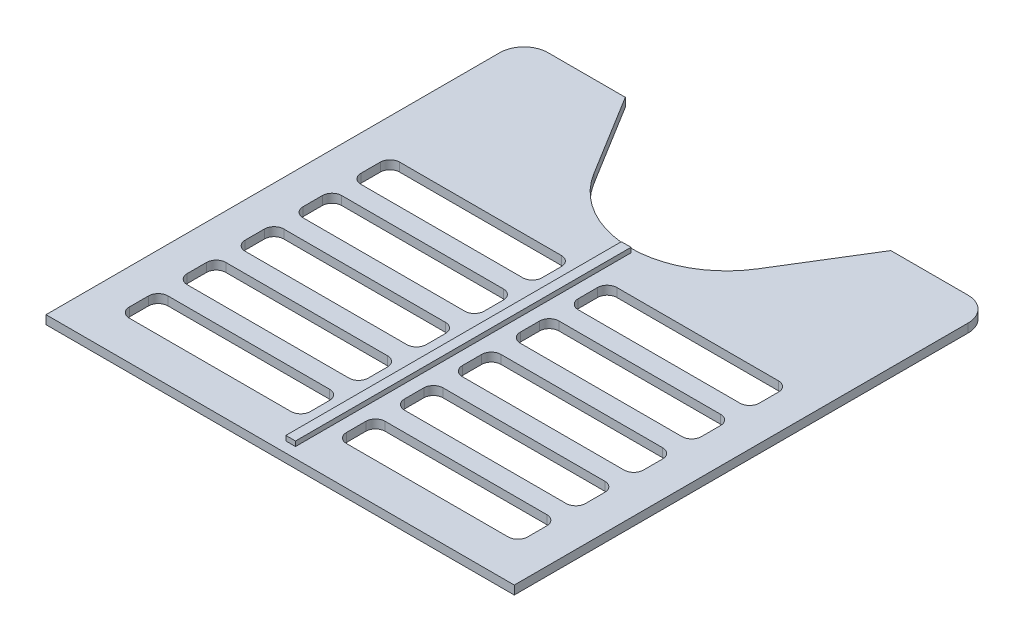
SolidWorks part; units mm, degrees
material "PVC hart"
ref_plane "Ebene vorne" through (0, 0, 0) normal (0, 0, 1) x (1, 0, 0)
ref_plane "Ebene oben" through (0, 0, 0) normal (0, 1, 0) x (1, 0, 0)
ref_plane "Ebene rechts" through (0, 0, 0) normal (1, 0, 0) x (0, 0, -1)
sketch "Skizze2" plane through (0, 0, 0) normal (0, 1, 0) x (1, 0, 0)
  line L0 (0, 82.3632) -> (0, -81.2206) construction
  line L6 (-43.5, 50) -> (-27.5, 50)
  line L7 (-27.5, 50) -> (-17.0289, 33)
  line L8 (27.5, 50) -> (17.0289, 33)
  line L9 (43.5, 50) -> (27.5, 50)
  line L10 (-48.5, -49) -> (-48.5, 45)
  line L11 (48.5, -49) -> (48.5, 45)
  line L12 (-48.5, -49) -> (48.5, -49)
  arc A0 (-17.0289, 33) -> (17.0289, 33) centre (0, 43.4889) ccw
  arc A1 (48.5, 45) -> (43.5, 50) centre (43.5, 45) ccw
  arc A2 (-48.5, 45) -> (-43.5, 50) centre (-43.5, 45) cw
  point P0 (0, 0)
  point P3 (48.5, 50)
  point P16 (-48.5, 50)
  dimension "D1" = 20
  dimension "D8" = 5
  dimension "D2" = 49
  dimension "D3" = 99
  dimension "D4" = 21
  dimension "D5" = 17
  dimension "D6" = 48.5
  dimension "D7" = 48.5
extrude "Grundkörper" add sketch "Skizze2" along normal blind 1.8
sketch "Skizze3" plane through (0, 1.8, 0) normal (0, 1, 0) x (1, 0, 0)
  line L0 (0, 51.615) -> (0, -55.1924) construction
  line L1 (-27.5, 50) -> (-43.5, 50) construction
  line L2 (-39.25, 15) -> (-5.75, 15)
  line L3 (-41.25, 13) -> (-41.25, 9)
  line L4 (-39.25, 7) -> (-5.75, 7)
  line L5 (-3.75, 13) -> (-3.75, 9)
  line L6 (-41.25, 15) -> (-3.75, 7) construction
  line L7 (-41.25, 7) -> (-3.75, 15) construction
  line L36 (3.75, 13) -> (3.75, 9)
  line L37 (5.75, 15) -> (39.25, 15)
  line L38 (41.25, 13) -> (41.25, 9)
  line L39 (5.75, 7) -> (39.25, 7)
  line L40 (3.75, 1) -> (3.75, -3)
  line L41 (5.75, 3) -> (39.25, 3)
  line L42 (41.25, 1) -> (41.25, -3)
  line L43 (5.75, -5) -> (39.25, -5)
  line L44 (3.75, -11) -> (3.75, -15)
  line L45 (5.75, -9) -> (39.25, -9)
  line L46 (41.25, -11) -> (41.25, -15)
  line L47 (5.75, -17) -> (39.25, -17)
  line L48 (3.75, -23) -> (3.75, -27)
  line L49 (5.75, -21) -> (39.25, -21)
  line L50 (41.25, -23) -> (41.25, -27)
  line L51 (5.75, -29) -> (39.25, -29)
  line L52 (3.75, -35) -> (3.75, -39)
  line L53 (5.75, -33) -> (39.25, -33)
  line L54 (41.25, -35) -> (41.25, -39)
  line L55 (5.75, -41) -> (39.25, -41)
  line L56 (-41.25, 1) -> (-41.25, -3)
  line L57 (-39.25, 3) -> (-5.75, 3)
  line L58 (-3.75, 1) -> (-3.75, -3)
  line L59 (-39.25, -5) -> (-5.75, -5)
  line L60 (-41.25, -11) -> (-41.25, -15)
  line L61 (-39.25, -9) -> (-5.75, -9)
  line L62 (-3.75, -11) -> (-3.75, -15)
  line L63 (-39.25, -17) -> (-5.75, -17)
  line L64 (-41.25, -23) -> (-41.25, -27)
  line L65 (-39.25, -21) -> (-5.75, -21)
  line L66 (-3.75, -23) -> (-3.75, -27)
  line L67 (-39.25, -29) -> (-5.75, -29)
  line L68 (-41.25, -35) -> (-41.25, -39)
  line L69 (-39.25, -33) -> (-5.75, -33)
  line L70 (-3.75, -35) -> (-3.75, -39)
  line L71 (-39.25, -41) -> (-5.75, -41)
  arc A0 (41.25, 9) -> (39.25, 7) centre (39.25, 9) cw
  arc A1 (39.25, 15) -> (41.25, 13) centre (39.25, 13) cw
  arc A2 (3.75, 13) -> (5.75, 15) centre (5.75, 13) cw
  arc A3 (3.75, 9) -> (5.75, 7) centre (5.75, 9) ccw
  arc A4 (3.75, -3) -> (5.75, -5) centre (5.75, -3) ccw
  arc A5 (3.75, 1) -> (5.75, 3) centre (5.75, 1) cw
  arc A6 (39.25, 3) -> (41.25, 1) centre (39.25, 1) cw
  arc A7 (41.25, -3) -> (39.25, -5) centre (39.25, -3) cw
  arc A8 (39.25, -9) -> (41.25, -11) centre (39.25, -11) cw
  arc A9 (41.25, -15) -> (39.25, -17) centre (39.25, -15) cw
  arc A10 (3.75, -15) -> (5.75, -17) centre (5.75, -15) ccw
  arc A11 (3.75, -11) -> (5.75, -9) centre (5.75, -11) cw
  arc A12 (3.75, -27) -> (5.75, -29) centre (5.75, -27) ccw
  arc A13 (3.75, -23) -> (5.75, -21) centre (5.75, -23) cw
  arc A14 (39.25, -21) -> (41.25, -23) centre (39.25, -23) cw
  arc A15 (41.25, -27) -> (39.25, -29) centre (39.25, -27) cw
  arc A16 (41.25, -39) -> (39.25, -41) centre (39.25, -39) cw
  arc A17 (39.25, -33) -> (41.25, -35) centre (39.25, -35) cw
  arc A18 (3.75, -39) -> (5.75, -41) centre (5.75, -39) ccw
  arc A19 (3.75, -35) -> (5.75, -33) centre (5.75, -35) cw
  arc A20 (-5.75, -33) -> (-3.75, -35) centre (-5.75, -35) cw
  arc A21 (-3.75, -39) -> (-5.75, -41) centre (-5.75, -39) cw
  arc A22 (-41.25, -39) -> (-39.25, -41) centre (-39.25, -39) ccw
  arc A23 (-41.25, -35) -> (-39.25, -33) centre (-39.25, -35) cw
  arc A24 (-5.75, -21) -> (-3.75, -23) centre (-5.75, -23) cw
  arc A25 (-3.75, -27) -> (-5.75, -29) centre (-5.75, -27) cw
  arc A26 (-41.25, -27) -> (-39.25, -29) centre (-39.25, -27) ccw
  arc A27 (-41.25, -23) -> (-39.25, -21) centre (-39.25, -23) cw
  arc A28 (-3.75, -15) -> (-5.75, -17) centre (-5.75, -15) cw
  arc A29 (-5.75, -9) -> (-3.75, -11) centre (-5.75, -11) cw
  arc A30 (-41.25, -15) -> (-39.25, -17) centre (-39.25, -15) ccw
  arc A31 (-41.25, -11) -> (-39.25, -9) centre (-39.25, -11) cw
  arc A32 (-3.75, -3) -> (-5.75, -5) centre (-5.75, -3) cw
  arc A33 (-5.75, 3) -> (-3.75, 1) centre (-5.75, 1) cw
  arc A34 (-41.25, -3) -> (-39.25, -5) centre (-39.25, -3) ccw
  arc A35 (-41.25, 1) -> (-39.25, 3) centre (-39.25, 1) cw
  arc A36 (-5.75, 7) -> (-3.75, 9) centre (-5.75, 9) ccw
  arc A37 (-41.25, 9) -> (-39.25, 7) centre (-39.25, 9) ccw
  arc A38 (-39.25, 15) -> (-41.25, 13) centre (-39.25, 13) ccw
  arc A39 (-5.75, 15) -> (-3.75, 13) centre (-5.75, 13) cw
  point P3 (-22.5, 11)
  dimension "D7" = 2
  dimension "D1" = 37.5
  dimension "D2" = 8
  dimension "D3" = 22.5
  dimension "D4" = 35
  dimension "D5" = 2
  dimension "D6" = 5
extrude "Lüftungen" cut sketch "Skizze3" against normal up to surface (1.8 mm away) up to face at (0, 0, -25.056)
sketch "Skizze4" plane through (0, 1.8, 0) normal (0, 1, 0) x (1, 0, 0)
  line L0 (0, 45.039) -> (0, -52.7268) construction
  line L1 (-1, 22.6826) -> (1, 22.6826)
  line L2 (-1, 22.6826) -> (-1, -46.8191)
  line L3 (-1, -46.8191) -> (1, -46.8191)
  line L4 (1, 22.6826) -> (1, -46.8191)
  dimension "D1" = 2
  dimension "D2" = 69.5018
extrude "Strebe" add sketch "Skizze4" along normal blind 1
